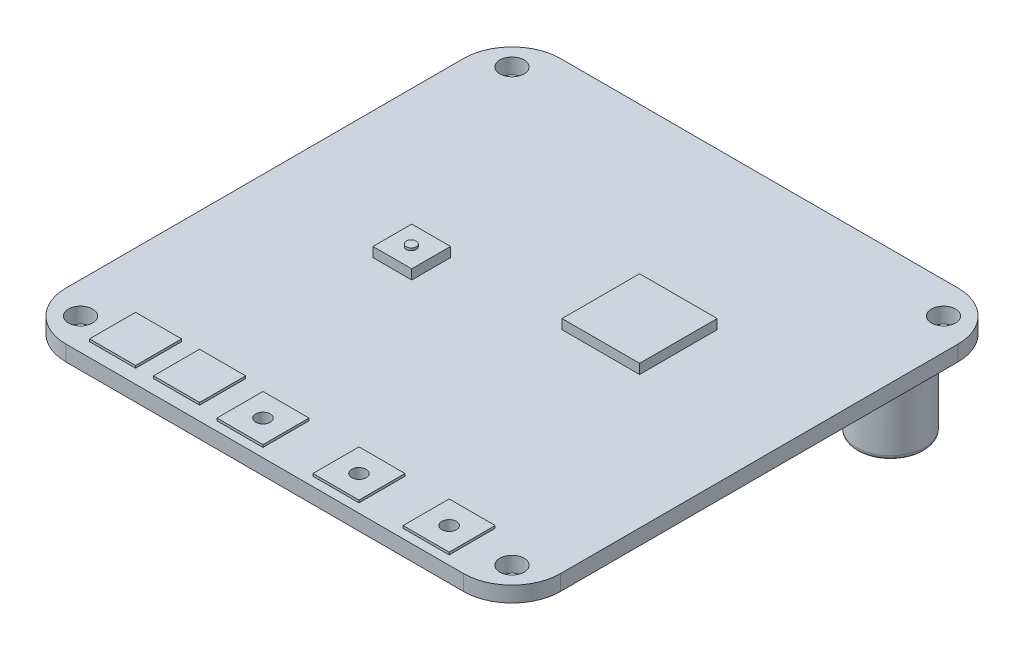
SolidWorks part; units mm, degrees
material "ABS"
ref_plane "Alzado" through (0, 0, 0) normal (0, 0, 1) x (1, 0, 0)
ref_plane "Planta" through (0, 0, 0) normal (0, 1, 0) x (1, 0, 0)
ref_plane "Vista lateral" through (0, 0, 0) normal (1, 0, 0) x (0, 0, -1)
sketch "Croquis1" plane through (0, 0, 0) normal (0, 1, 0) x (1, 0, 0)
  line L1 (-25.5, 25.5) -> (25.5, 25.5)
  line L2 (-25.5, 25.5) -> (-25.5, -25.5)
  line L3 (-25.5, -25.5) -> (25.5, -25.5)
  line L4 (25.5, 25.5) -> (25.5, -25.5)
  line L5 (-25.5, 25.5) -> (25.5, -25.5) construction
  line L6 (-25.5, -25.5) -> (25.5, 25.5) construction
  point P0 (0, 0)
  dimension "D1" = 51
  dimension "D2" = 51
extrude "Saliente-Extruir1" add sketch "Croquis1" against normal blind 1.6
fillet "Redondeo1" radius 5 4 edges at (25.5, -0.8, -25.5) (-25.5, -0.8, -25.5) (-25.5, -0.8, 25.5) (25.5, -0.8, 25.5)
sketch "Croquis2" plane through (0, 0, 0) normal (0, 1, 0) x (1, 0, 0)
  line L0 (-25.5, 20.5) -> (-25.5, -20.5) construction
  line L1 (-12.3871, 2.0474) -> (-8.3871, 2.0474)
  line L2 (-12.3871, 2.0474) -> (-12.3871, -1.9526)
  line L3 (-12.3871, -1.9526) -> (-8.3871, -1.9526)
  line L4 (-8.3871, 2.0474) -> (-8.3871, -1.9526)
  line L5 (-12.3871, 2.0474) -> (-8.3871, -1.9526) construction
  line L6 (-12.3871, -1.9526) -> (-8.3871, 2.0474) construction
  line L7 (3.8, 9.359) -> (11.8, 9.359)
  line L8 (3.8, 9.359) -> (3.8, 1.359)
  line L9 (3.8, 1.359) -> (11.8, 1.359)
  line L10 (11.8, 9.359) -> (11.8, 1.359)
  line L11 (3.8, 9.359) -> (11.8, 1.359) construction
  line L12 (3.8, 1.359) -> (11.8, 9.359) construction
  line L13 (25.5, -20.5) -> (25.5, 20.5) construction
  point P0 (-10.3871, 0.0474)
  point P5 (7.8, 5.359)
  point P12 (-25.5, 0)
  dimension "D1" = 15.113
  dimension "D2" = 4
  dimension "D3" = 8
  dimension "D4" = 17.7
extrude "Saliente-Extruir2" add sketch "Croquis2" along normal blind 1
sketch "Croquis3" plane through (0, 0, 0) normal (0, 1, 0) x (1, 0, 0)
  line L1 (22.25, 22.25) -> (-22.25, 22.25) construction
  line L2 (22.25, 22.25) -> (22.25, -22.25) construction
  line L3 (22.25, -22.25) -> (-22.25, -22.25) construction
  line L4 (-22.25, 22.25) -> (-22.25, -22.25) construction
  line L5 (22.25, 22.25) -> (-22.25, -22.25) construction
  line L6 (22.25, -22.25) -> (-22.25, 22.25) construction
  circle A0 centre (-22.25, 22.25) radius 1.25
  circle A1 centre (-22.25, -22.25) radius 1.25
  circle A2 centre (22.25, -22.25) radius 1.25
  circle A3 centre (22.25, 22.25) radius 1.25
  point P0 (0, 0)
  dimension "D2" = 2.5
  dimension "D1" = 44.5
extrude "Cortar-Extruir1" cut sketch "Croquis3" against normal through all
sketch "Croquis4" plane through (0, 0, 0) normal (0, 1, 0) x (1, 0, 0)
  line L0 (-20.5, -25.5) -> (20.5, -25.5) construction
  line L1 (-5.855, -19.825) -> (-1.105, -19.825)
  line L2 (-5.855, -19.825) -> (-5.855, -24.575)
  line L3 (-5.855, -24.575) -> (-1.105, -24.575)
  line L4 (-1.105, -19.825) -> (-1.105, -24.575)
  line L5 (-5.855, -19.825) -> (-1.105, -24.575) construction
  line L6 (-5.855, -24.575) -> (-1.105, -19.825) construction
  line L7 (4.045, -19.825) -> (8.795, -19.825)
  line L8 (4.045, -19.825) -> (4.045, -24.575)
  line L9 (4.045, -24.575) -> (8.795, -24.575)
  line L10 (8.795, -19.825) -> (8.795, -24.575)
  line L11 (4.045, -19.825) -> (8.795, -24.575) construction
  line L12 (4.045, -24.575) -> (8.795, -19.825) construction
  line L13 (13.345, -19.825) -> (18.095, -19.825)
  line L14 (13.345, -19.825) -> (13.345, -24.575)
  line L15 (13.345, -24.575) -> (18.095, -24.575)
  line L16 (18.095, -19.825) -> (18.095, -24.575)
  line L17 (13.345, -19.825) -> (18.095, -24.575) construction
  line L18 (13.345, -24.575) -> (18.095, -19.825) construction
  line L19 (25.5, -20.5) -> (25.5, 20.5) construction
  line L20 (-25.5, 20.5) -> (-25.5, -20.5) construction
  line L21 (-12.895, -19.325) -> (-8.145, -19.325)
  line L22 (-12.895, -19.325) -> (-12.895, -24.075)
  line L23 (-12.895, -24.075) -> (-8.145, -24.075)
  line L24 (-8.145, -19.325) -> (-8.145, -24.075)
  line L25 (-12.895, -19.325) -> (-8.145, -24.075) construction
  line L26 (-12.895, -24.075) -> (-8.145, -19.325) construction
  line L27 (-19.495, -19.325) -> (-14.745, -19.325)
  line L28 (-19.495, -19.325) -> (-19.495, -24.075)
  line L29 (-19.495, -24.075) -> (-14.745, -24.075)
  line L30 (-14.745, -19.325) -> (-14.745, -24.075)
  line L31 (-19.495, -19.325) -> (-14.745, -24.075) construction
  line L32 (-19.495, -24.075) -> (-14.745, -19.325) construction
  point P0 (-3.48, -22.2)
  point P5 (6.42, -22.2)
  point P10 (15.72, -22.2)
  point P17 (0, -25.5)
  point P18 (-17.12, -21.7)
  point P21 (-10.52, -21.7)
  dimension "D1" = 3.3
  dimension "D2" = 4.75
  dimension "D3" = 9.9
  dimension "D4" = 9.3
  dimension "D5" = 9.78
  dimension "D6" = 4.75
  dimension "D7" = 3.8
  dimension "D8" = 6.6
  dimension "D9" = 8.38
extrude "Saliente-Extruir3" add sketch "Croquis4" along normal blind 0.25
sketch "Croquis5" plane through (0, 0.25, 0) normal (0, 1, 0) x (1, 0, 0)
  line L0 (-1.105, -19.825) -> (-5.855, -19.825) construction
  line L1 (-5.855, -19.825) -> (-5.855, -24.575) construction
  line L2 (8.795, -19.825) -> (4.045, -19.825) construction
  line L3 (18.095, -19.825) -> (13.345, -19.825) construction
  circle A0 centre (-3.48, -22.2) radius 0.75
  circle A1 centre (6.42, -22.2) radius 0.75
  circle A2 centre (15.72, -22.2) radius 0.75
  point P9 (-3.48, -19.825)
  point P12 (-5.855, -22.2)
  point P16 (6.42, -19.825)
  point P19 (15.72, -19.825)
  dimension "D1" = 1.5
extrude "Cortar-Extruir2" cut sketch "Croquis5" against normal through all
sketch "Croquis6" plane through (0, -1.6, 0) normal (0, 1, 0) x (1, 0, 0)
  circle A0 centre (-16.2367, 22.6268) radius 3.5
  circle A1 centre (16.4107, 22.6268) radius 3.5
  point P4 (16.4107, 22.8387)
  point P5 (-16.2367, 22.6268)
  dimension "D1" = 7
extrude "Saliente-Extruir4" add sketch "Croquis6" against normal blind 12
fillet "Redondeo2" radius 0.5 2 edges at (16.4107, -13.6, -19.1268) (-16.2367, -13.6, -19.1268)
sketch "Croquis7" plane through (0, -1.6, 0) normal (0, -1, 0) x (1, 0, 0)
  line L0 (-20.5, 25.5) -> (20.5, 25.5) construction
  line L1 (-22.5, -16.02) -> (15.6, -16.02)
  line L2 (-22.5, -16.02) -> (-22.5, -18.56)
  line L3 (-22.5, -18.56) -> (15.6, -18.56)
  line L4 (15.6, -16.02) -> (15.6, -18.56)
  line L5 (-22.5, -16.02) -> (15.6, -18.56) construction
  line L6 (-22.5, -18.56) -> (15.6, -16.02) construction
  line L7 (-22.5, 9.33) -> (15.6, 9.33)
  line L8 (-22.5, 9.33) -> (-22.5, 6.79)
  line L9 (-22.5, 6.79) -> (15.6, 6.79)
  line L10 (15.6, 9.33) -> (15.6, 6.79)
  line L11 (-22.5, 9.33) -> (15.6, 6.79) construction
  line L12 (-22.5, 6.79) -> (15.6, 9.33) construction
  line L13 (-25.5, -20.5) -> (-25.5, 20.5) construction
  point P0 (-3.45, -17.29)
  point P5 (-3.45, 8.06)
  dimension "D1" = 17.44
  dimension "D2" = 25.35
  dimension "D3" = 38.1
  dimension "D4" = 2.54
  dimension "D5" = 2.54
  dimension "D6" = 3
extrude "Saliente-Extruir5" add sketch "Croquis7" along normal blind 8
sketch "Croquis8" plane through (0, 1, 0) normal (0, 1, 0) x (1, 0, 0)
  line L0 (-8.3871, 2.0474) -> (-12.3871, 2.0474) construction
  circle A0 centre (-10.3871, 0) radius 0.5121
  point P5 (-10.3871, 2.0474)
extrude "Saliente-Extruir6" add sketch "Croquis8" along normal blind 0.25
